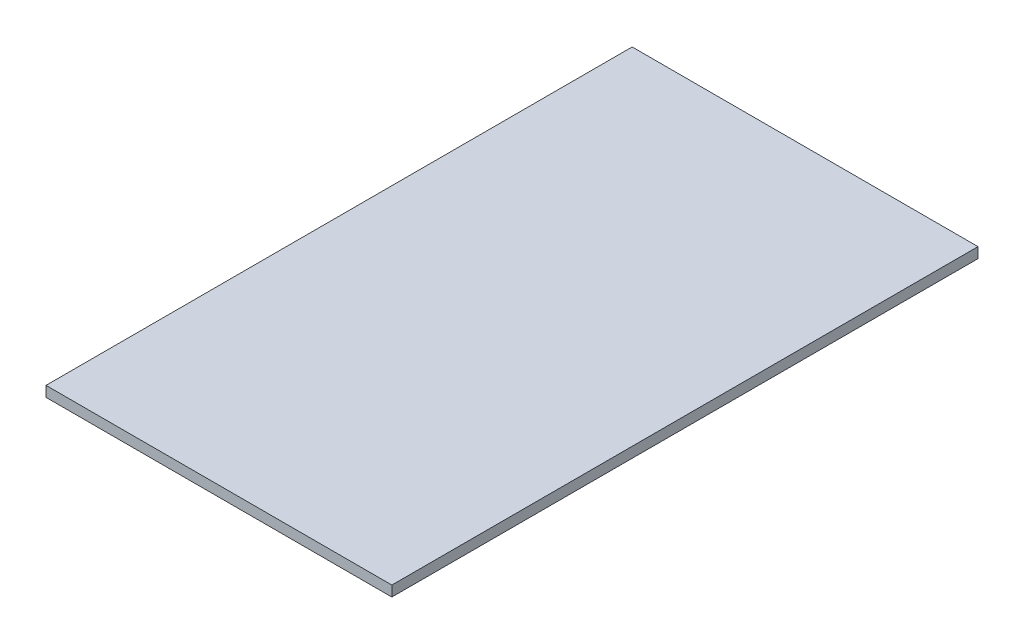
SolidWorks part; units mm, degrees
ref_plane "Alzado" through (0, 0, 0) normal (0, 0, 1) x (1, 0, 0)
ref_plane "Planta" through (0, 0, 0) normal (0, 1, 0) x (1, 0, 0)
ref_plane "Vista lateral" through (0, 0, 0) normal (1, 0, 0) x (0, 0, -1)
sketch "Croquis1" plane through (0, 254.7071, 0) normal (0, 1, 0) x (1, 0, 0)
  line L0 (80.653, -490) -> (80.653, -40) construction
  line L1 (-184.852, -490) -> (-184.852, -40) construction
  line L2 (80.653, -490) -> (80.653, -40) construction
  line L3 (-184.852, -490) -> (-184.852, -40) construction
  line L5 (-184.852, -40) -> (80.653, -40)
  line L6 (-184.852, -40) -> (-184.852, -490)
  line L7 (-184.852, -490) -> (80.653, -490)
  line L8 (80.653, -40) -> (80.653, -490)
extrude "Saliente-Extruir1" add sketch "Croquis1" along normal mid plane 8
